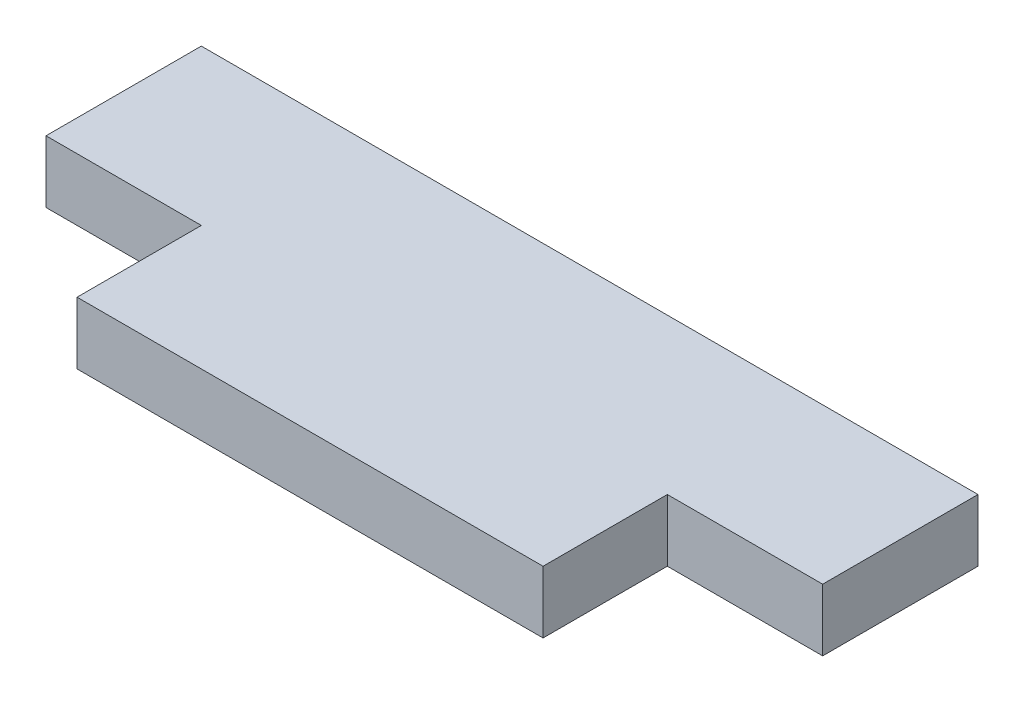
SolidWorks part; units mm, degrees
ref_plane "Front Plane" through (0, 0, 0) normal (0, 0, 1) x (1, 0, 0)
ref_plane "Top Plane" through (0, 0, 0) normal (0, 1, 0) x (1, 0, 0)
ref_plane "Right Plane" through (0, 0, 0) normal (1, 0, 0) x (0, 0, -1)
sketch "Sketch1" plane through (0, 0, 0) normal (0, 0, 1) x (1, 0, 0)
  line L1 (-7.5, 1) -> (7.5, 1)
  line L2 (-7.5, 1) -> (-7.5, -1)
  line L3 (-7.5, -1) -> (7.5, -1)
  line L4 (7.5, 1) -> (7.5, -1)
  dimension "D1" = 15
  dimension "D2" = 2
  dimension "D3" = 1
  dimension "D4" = 7.5
extrude "Boss-Extrude1" add sketch "Sketch1" along normal blind 4
sketch "Sketch2" plane through (0, 0, 0) normal (0, 0, -1) x (-1, 0, 0)
  line L0 (7.5, -1) -> (-7.5, -1) construction
  line L1 (12.5, 1) -> (-12.5, 1)
  line L2 (12.5, 1) -> (12.5, -1)
  line L3 (12.5, -1) -> (-12.5, -1)
  line L4 (-12.5, 1) -> (-12.5, -1)
  line L5 (-7.5, 1) -> (7.5, 1) construction
  line L6 (-7.5, -1) -> (-7.5, 1) construction
  line L7 (7.5, 1) -> (7.5, -1) construction
  dimension "D1" = 5
  dimension "D2" = 5
extrude "Boss-Extrude2" add sketch "Sketch2" along normal blind 5
